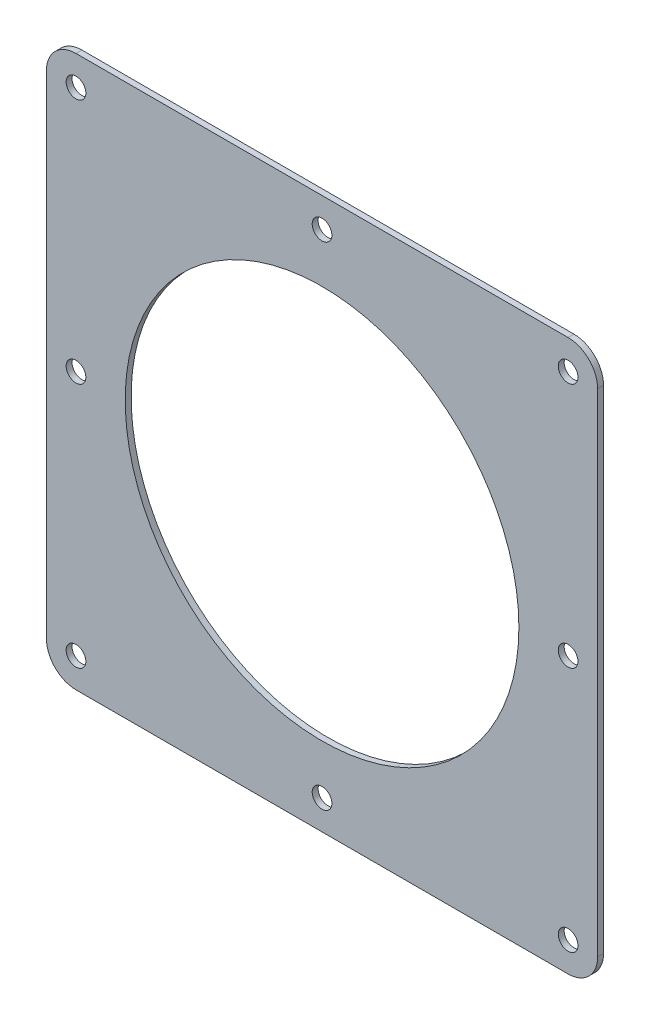
SolidWorks part; units mm, degrees
ref_plane "Front Plane" through (0, 0, 0) normal (0, 0, 1) x (1, 0, 0)
ref_plane "Top Plane" through (0, 0, 0) normal (0, 1, 0) x (1, 0, 0)
ref_plane "Right Plane" through (0, 0, 0) normal (1, 0, 0) x (0, 0, -1)
sketch "Sketch2" plane through (0, 0, 0) normal (0, 0, 1) x (1, 0, 0)
  line L0 (-125, 125) -> (125, 125) construction
  line L1 (-125, 140) -> (125, 140)
  line L2 (-140, 125) -> (-140, -125)
  line L3 (-125, -140) -> (125, -140)
  line L4 (140, 125) -> (140, -125)
  line L5 (-140, 140) -> (140, -140) construction
  line L6 (-140, -140) -> (140, 140) construction
  line L7 (125, 125) -> (125, -125) construction
  line L8 (125, -125) -> (-125, -125) construction
  line L9 (-125, -125) -> (-125, 125) construction
  arc A0 (-140, -125) -> (-125, -140) centre (-125, -125) ccw
  arc A1 (125, -140) -> (140, -125) centre (125, -125) ccw
  arc A2 (125, 140) -> (140, 125) centre (125, 125) cw
  arc A3 (-125, 140) -> (-140, 125) centre (-125, 125) ccw
  circle A4 centre (-125, 125) radius 5
  circle A5 centre (0, 125) radius 5
  circle A6 centre (125, 125) radius 5
  circle A13 centre (0, 0) radius 4
  circle A14 centre (125, 0) radius 5
  circle A15 centre (-125, 0) radius 5
  circle A16 centre (-125, -125) radius 5
  circle A17 centre (0, -125) radius 5
  circle A18 centre (125, -125) radius 5
  point P0 (0, 0)
  dimension "D3" = 15
  dimension "D4" = 10
  dimension "D5" = 10
  dimension "D6" = 10
  dimension "D7" = 8
  dimension "D8" = 10
  dimension "D9" = 10
  dimension "D10" = 10
  dimension "D11" = 10
  dimension "D1" = 280
  dimension "D2" = 280
extrude "Boss-Extrude1" add sketch "Sketch2" along normal blind 3
sketch "Sketch7" plane through (0, 0, 3) normal (0, 0, 1) x (1, 0, 0)
  circle A0 centre (0, 0) radius 100
  dimension "D1" = 200
extrude "Cut-Extrude2" cut sketch "Sketch7" against normal blind 10
